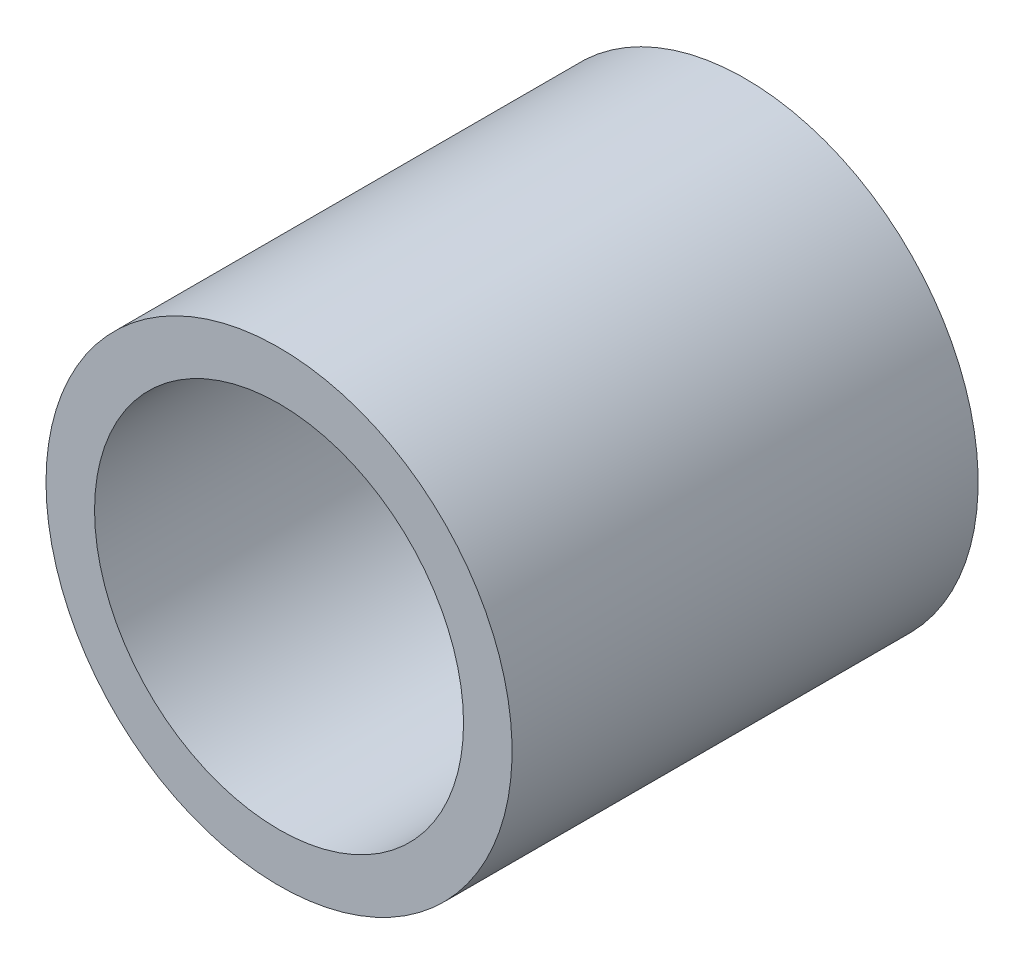
SolidWorks part; units mm, degrees
material "6061 Alloy"
ref_plane "Front Plane" through (0, 0, 0) normal (0, 0, 1) x (1, 0, 0)
ref_plane "Top Plane" through (0, 0, 0) normal (0, 1, 0) x (1, 0, 0)
ref_plane "Right Plane" through (0, 0, 0) normal (1, 0, 0) x (0, 0, -1)
sketch "Sketch1" plane through (0, 0, 0) normal (0, 0, 1) x (1, 0, 0)
  circle A0 centre (0, 0) radius 7.5406
  circle A1 centre (0, 0) radius 9.525
  dimension "D1" = 19.05
  dimension "19/32" = 15.0812
extrude "Boss-Extrude1" add sketch "Sketch1" along normal mid plane 19.05
